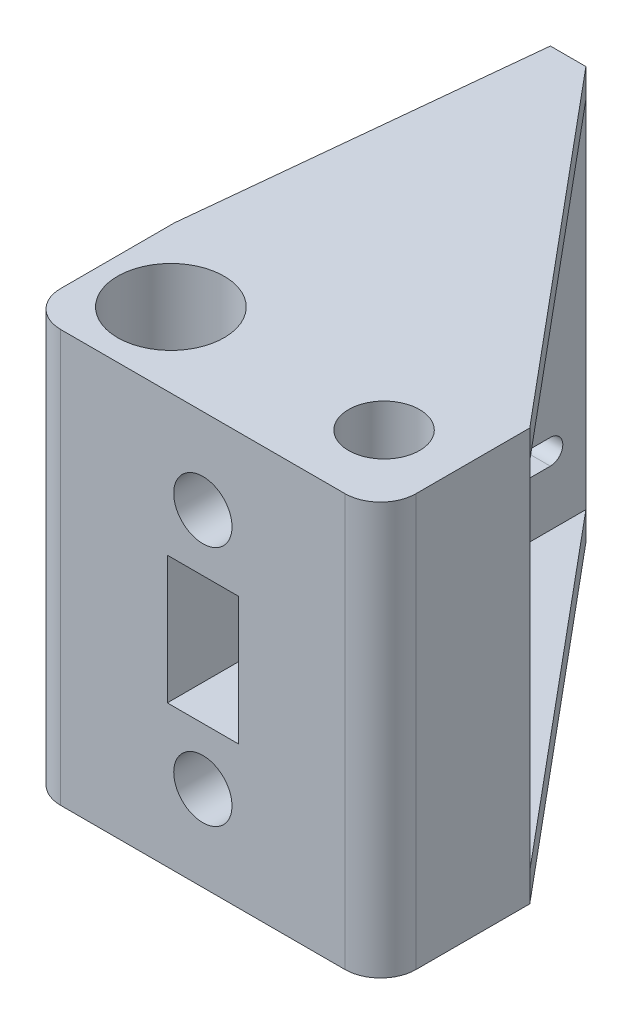
SolidWorks part; units mm, degrees
ref_plane "Front Plane" through (0, 0, 0) normal (0, 0, 1) x (1, 0, 0)
ref_plane "Top Plane" through (0, 0, 0) normal (0, 1, 0) x (1, 0, 0)
ref_plane "Right Plane" through (0, 0, 0) normal (1, 0, 0) x (0, 0, -1)
sketch "Sketch1" plane through (0, 0, 0) normal (0, 1, 0) x (1, 0, 0)
  line L1 (-25, 10.5) -> (25, 10.5)
  line L2 (-25, 10.5) -> (-25, -10.5)
  line L3 (-25, -10.5) -> (25, -10.5)
  line L4 (25, 10.5) -> (25, -10.5)
  line L5 (-25, 10.5) -> (25, -10.5) construction
  line L6 (-25, -10.5) -> (25, 10.5) construction
  point P0 (0, 0)
  dimension "D1" = 21
  dimension "D2" = 50
extrude "Boss-Extrude1" add sketch "Sketch1" along normal blind 58
sketch "Sketch3" plane through (0, 58, 0) normal (0, 1, 0) x (1, 0, 0)
  line L0 (-15, 0) -> (15, 0) construction
  circle A0 centre (-15, 0) radius 7.5
  dimension "D1" = 15
  dimension "D2" = 30
extrude "Cut-Extrude1" cut sketch "Sketch3" against normal blind 24 contours A0
sketch "Sketch4" plane through (0, 58, 0) normal (0, 1, 0) x (1, 0, 0)
  line L0 (-15, 0) -> (15, 0) construction
  circle A0 centre (15, 0) radius 5
  dimension "D1" = 10
extrude "Cut-Extrude2" cut sketch "Sketch4" against normal up to next
sketch "Sketch5" plane through (0, 0, 0) normal (0, -1, 0) x (1, 0, 0)
  circle A1 centre (-15, 0) radius 7.5
  circle A2 centre (-15, 0) radius 7.5
  dimension "D1" = 0
extrude "Cut-Extrude3" cut sketch "Sketch5" against normal blind 24
sketch "Sketch6" plane through (0, 0, 0) normal (0, -1, 0) x (1, 0, 0)
  circle A0 centre (-15, 0) radius 4.5
extrude "Cut-Extrude4" cut sketch "Sketch6" against normal up to next
sketch "Sketch7" plane through (0, 0, 10.5) normal (0, 0, 1) x (1, 0, 0)
  line L0 (0, 58) -> (0, 0) construction
  line L1 (-25, 58) -> (25, 58) construction
  line L2 (-25, 0) -> (25, 0) construction
  line L3 (-25, 29) -> (25, 29) construction
  line L4 (-25, 58) -> (-25, 0) construction
  line L5 (25, 58) -> (25, 0) construction
  circle A1 centre (0, 46) radius 4.1
  circle A2 centre (0, 12) radius 4.1
  point P24 (0, 12)
  dimension "D1" = 8.2
  dimension "D2" = 12
sketch "Sketch8" plane through (0, 0, 10.5) normal (0, 0, 1) x (1, 0, 0)
  line L0 (-25, 29) -> (25, 29) construction
  line L1 (-25, 58) -> (-25, 0) construction
  line L2 (25, 58) -> (25, 0) construction
  line L3 (0, 58) -> (0, 0) construction
  line L4 (-25, 58) -> (25, 58) construction
  line L6 (-5, 20) -> (5, 20)
  line L7 (-5, 20) -> (-5, 38)
  line L8 (-5, 38) -> (5, 38)
  line L9 (5, 20) -> (5, 38)
  line L10 (-5, 20) -> (5, 38) construction
  line L11 (-5, 38) -> (5, 20) construction
  point P11 (0, 29)
  dimension "D1" = 18
  dimension "D2" = 10
extrude "Cut-Extrude5" cut sketch "Sketch8" against normal up to next
sketch "Sketch9" plane through (0, 0, -10.5) normal (0, 0, -1) x (-1, 0, 0)
  line L0 (0, 58) -> (0, 0) construction
  line L1 (-25, 58) -> (25, 58) construction
  line L2 (-25, 29) -> (25, 29) construction
  line L3 (-25, 58) -> (-25, 0) construction
  line L4 (25, 58) -> (25, 0) construction
  line L5 (15.1, 58) -> (15.1, 0)
  line L6 (-25, 0) -> (25, 0) construction
  line L7 (15.1, 0) -> (20.1, 0)
  line L8 (20.1, 0) -> (20.1, 58)
  line L9 (20.1, 58) -> (15.1, 58)
  dimension "D1" = 20.1
  dimension "D2" = 5
extrude "Boss-Extrude3" add sketch "Sketch9" along normal blind 48
sketch "Sketch10" plane through (-20.1, 0, 0) normal (-1, 0, 0) x (0, 0, 1)
  line L0 (-58.5, 29) -> (-10.5, 29) construction
  line L1 (-58.5, 0) -> (-58.5, 58) construction
  line L4 (-10.5, 58) -> (-10.5, 0) construction
  line L11 (-34.5, 0) -> (-34.5, 58) construction
  line L12 (-58.5, 0) -> (-10.5, 0) construction
  line L13 (-58.5, 58) -> (-10.5, 58) construction
  line L14 (-15.5, 44.45) -> (-53.5, 44.45) construction
  line L15 (-41.5, 17) -> (-27.5, 17)
  line L16 (-46.5, 22) -> (-46.5, 36)
  line L17 (-41.5, 41) -> (-27.5, 41)
  line L18 (-22.5, 22) -> (-22.5, 36)
  line L19 (-46.5, 17) -> (-22.5, 41) construction
  line L20 (-46.5, 41) -> (-22.5, 17) construction
  line L23 (-15.5, 42.7) -> (-53.5, 42.7)
  line L26 (-15.5, 46.2) -> (-53.5, 46.2)
  line L27 (-15.5, 13.55) -> (-53.5, 13.55) construction
  line L28 (-15.5, 15.3) -> (-53.5, 15.3)
  line L29 (-15.5, 11.8) -> (-53.5, 11.8)
  arc A8 (-27.5, 17) -> (-22.5, 22) centre (-27.5, 22) ccw
  arc A9 (-22.5, 36) -> (-27.5, 41) centre (-27.5, 36) ccw
  arc A10 (-41.5, 41) -> (-46.5, 36) centre (-41.5, 36) ccw
  arc A11 (-41.5, 17) -> (-46.5, 22) centre (-41.5, 22) cw
  arc A16 (-15.5, 42.7) -> (-15.5, 46.2) centre (-15.5, 44.45) ccw
  arc A17 (-53.5, 46.2) -> (-53.5, 42.7) centre (-53.5, 44.45) ccw
  arc A18 (-15.5, 15.3) -> (-15.5, 11.8) centre (-15.5, 13.55) cw
  arc A19 (-53.5, 11.8) -> (-53.5, 15.3) centre (-53.5, 13.55) cw
  point P12 (-34.5, 29)
  point P31 (-34.5, 44.45)
  point P38 (-34.5, 13.55)
  dimension "D3" = 5
  dimension "D1" = 24
  dimension "D2" = 24
  dimension "D4" = 1.75
  dimension "D5" = 15.45
  dimension "D6" = 19
extrude "Cut-Extrude7" cut sketch "Sketch10" against normal up to next
ref_plane "Plane1" through (0, 0, 0) normal (0, -1, 0) x (-1, 0, 0)
ref_plane "Plane2" through (0, 29, 0) normal (0, -1, 0) x (-1, 0, 0)
sketch "Sketch11" plane through (0, 0, 0) normal (0, -1, 0) x (-1, 0, 0)
  line L0 (15.1, 58.5) -> (-25, 10.5)
  line L1 (-25, 10.5) -> (15.1, 10.5)
  line L2 (15.1, 10.5) -> (15.1, 58.5)
  line L3 (20.1, 58.5) -> (20.1, 10.5)
  line L4 (20.1, 10.5) -> (25, 10.5)
  line L5 (25, 10.5) -> (20.1, 58.5)
extrude "Boss-Extrude4" add sketch "Sketch11" against normal blind 4
mirror "Mirror1" about plane through (0, 29, 0) normal (0, -1, 0) of "Boss-Extrude4"
fillet "Fillet1" radius 5 2 edges at (25, 29, 10.5) (-25, 29, 10.5)
extrude "Cut-Extrude8" cut sketch "Sketch7" against normal blind 15
